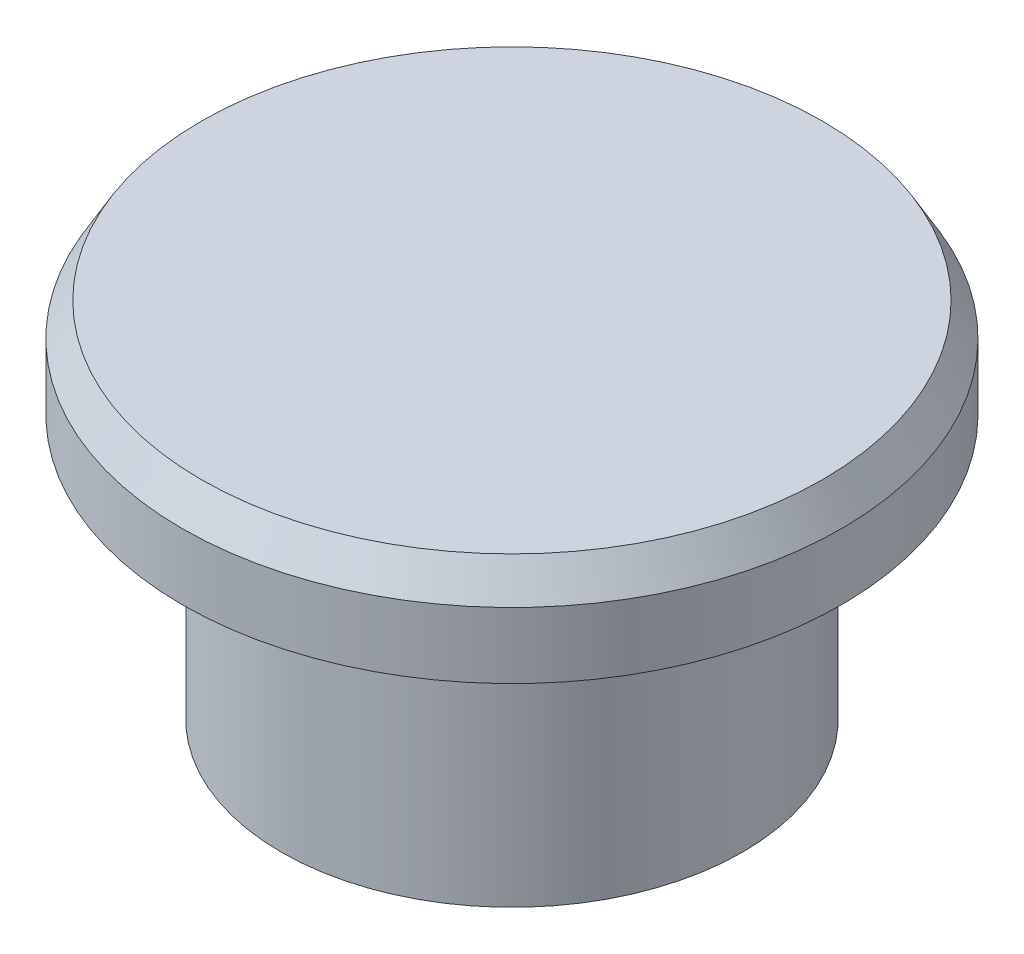
SolidWorks part; units mm, degrees
ref_plane "Plan de face" through (0, 0, 0) normal (0, 0, 1) x (1, 0, 0)
ref_plane "Plan de dessus" through (0, 0, 0) normal (0, 1, 0) x (1, 0, 0)
ref_plane "Plan de droite" through (0, 0, 0) normal (1, 0, 0) x (0, 0, -1)
sketch "Esquisse1" plane through (0, 0, 0) normal (0, 1, 0) x (1, 0, 0)
  circle A0 centre (0, 0) radius 14
extrude "Boss.-Extru.1" add sketch "Esquisse1" along normal blind 14
sketch "Esquisse2" plane through (0, 14, 0) normal (0, 1, 0) x (1, 0, 0)
  circle A0 centre (0, 0) radius 10.5
extrude "Boss.-Extru.2" add sketch "Esquisse2" along normal blind 2
sketch "Esquisse4" plane through (0, 16, 0) normal (0, 1, 0) x (1, 0, 0)
  circle A0 centre (0, 0) radius 20
extrude "Boss.-Extru.3" add sketch "Esquisse4" along normal blind 4
sketch "Esquisse5" plane through (0, 20, 0) normal (0, 1, 0) x (1, 0, 0)
  circle A0 centre (0, 0) radius 20
extrude "Boss.-Extru.4" add sketch "Esquisse5" along normal blind 2
chamfer "Chanfrein1" distance 2 angle 30 1 edges at (0, 22, 20)
